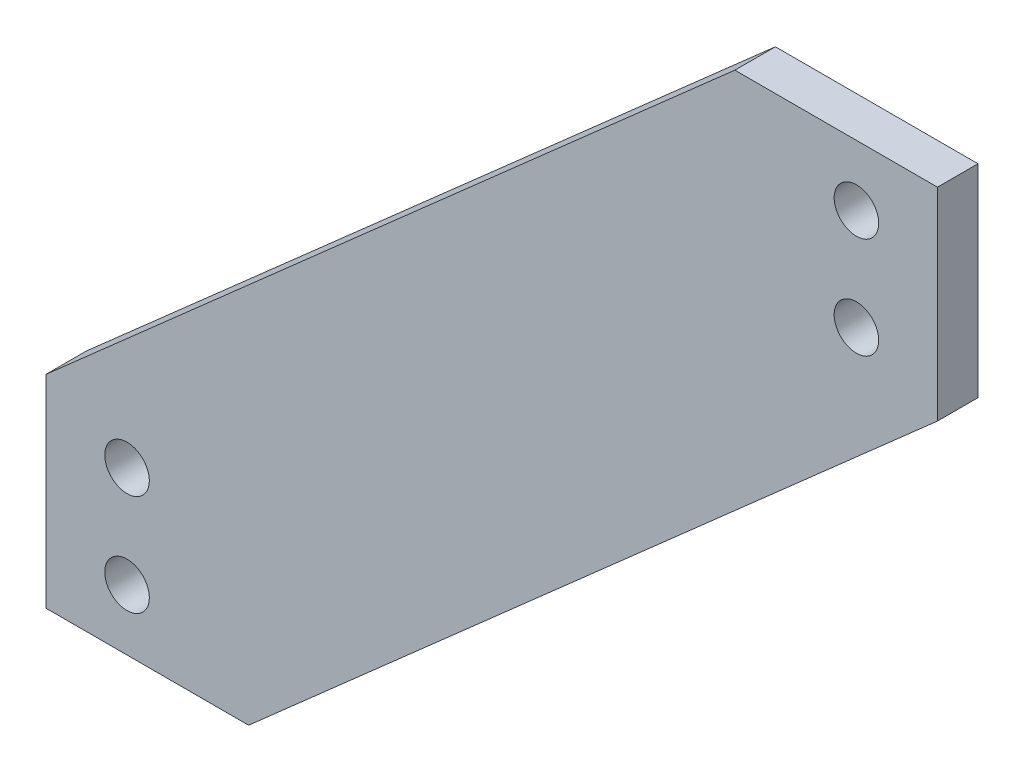
SolidWorks part; units mm, degrees
ref_plane "Front" through (0, 0, 0) normal (0, 0, 1) x (1, 0, 0)
ref_plane "Top" through (0, 0, 0) normal (0, 1, 0) x (1, 0, 0)
ref_plane "Right" through (0, 0, 0) normal (1, 0, 0) x (0, 0, -1)
sketch "Sketch1" plane through (0, 0, 0) normal (0, 0, 1) x (1, 0, 0)
  line L0 (0, 0) -> (20, 0)
  line L1 (20, 0) -> (110, 100)
  line L2 (110, 100) -> (90, 100)
  line L3 (90, 100) -> (0, 0)
  dimension "D1" = 20
  dimension "D2" = 100
  dimension "D3" = 110
extrude "Boss-Extrude1" add sketch "Sketch1" along normal blind 5
sketch "Sketch2" plane through (0, 0, 5) normal (0, 0, 1) x (1, 0, 0)
  line L0 (0, 0) -> (0, 25)
  line L1 (0, 25) -> (85, 100)
  line L2 (0, 0) -> (25, 0)
  line L3 (90, 100) -> (85, 100)
  line L4 (110, 100) -> (110, 75)
  line L5 (110, 75) -> (25, 0)
  line L8 (90, 100) -> (110, 100)
  dimension "D1" = 25
  dimension "D2" = 25
  dimension "D3" = 25
extrude "Boss-Extrude2" add sketch "Sketch2" against normal up to surface (5 mm away) up to face at (55, 50, 0)
hole_wizard "M5 Clearance Hole1" positions "Sketch3" profile "Sketch4" hole size "M5" standard "ISO" end condition through all
sketch "Sketch3" plane through (0, 0, 5) normal (0, 0, 1) x (1, 0, 0)
  line L0 (0, 25) -> (0, 0) construction
  line L1 (0, 0) -> (25, 0) construction
  line L2 (110, 100) -> (85, 100) construction
  line L3 (110, 75) -> (110, 100) construction
  line L4 (10, 20) -> (10, 0) construction
  line L6 (100, 80) -> (100, 100) construction
  point P0 (100, 80)
  point P2 (10, 20)
  point P21 (10, 7.5)
  point P23 (100, 92.5)
  point P26 (0, 0)
  point P27 (10, 6.6111)
  point P28 (0, 0)
  point P29 (100, 93.2454)
  dimension "D1" = 10
  dimension "D2" = 20
  dimension "D3" = 20
  dimension "D4" = 10
  dimension "D5" = 12.5
  dimension "D6" = 12.5
sketch "Sketch4" plane through (100, 80, 5) normal (1, 0, 0) x (0, -1, 0)
  line L0 (0, 0) -> (0, 5)
  line L1 (0, 5) -> (2.75, 5)
  line L2 (2.75, 5) -> (2.75, 0)
  line L5 (2.75, 0) -> (0, 0)
  line L11 (0, -6.35) -> (0, 107.95) construction
  dimension "Thru Hole Dia." = 5.5
  dimension "Thru Hole Depth" = 5
